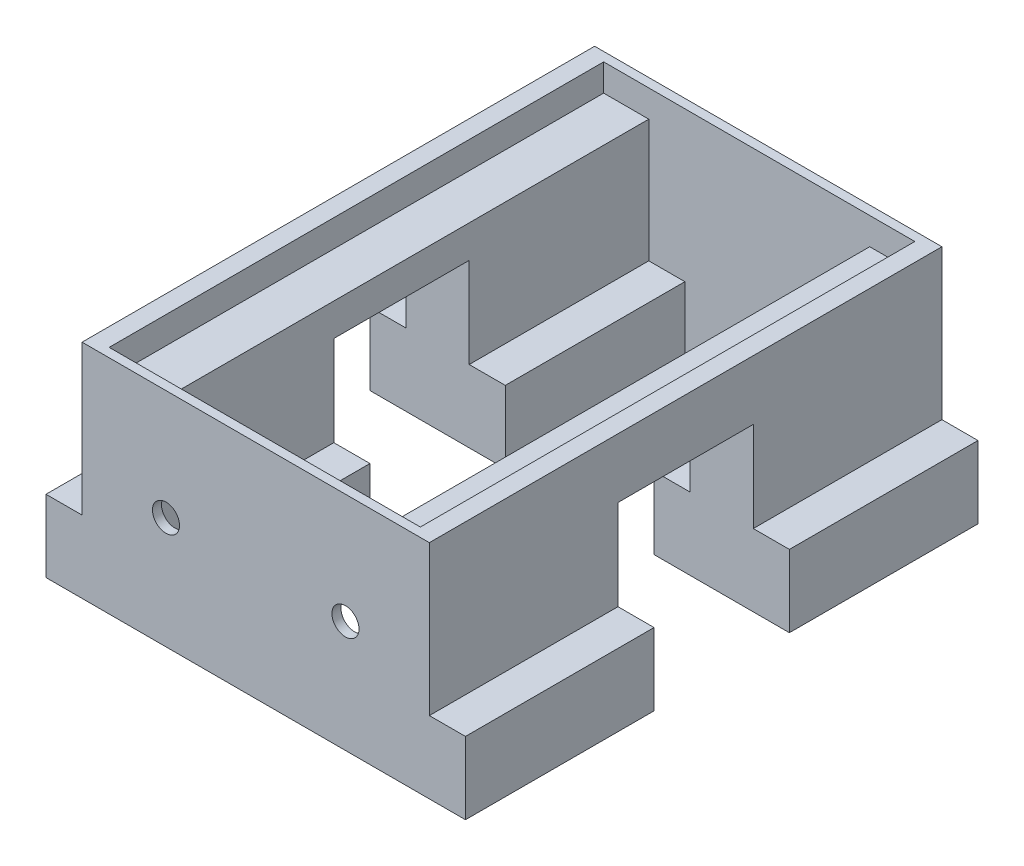
SolidWorks part; units mm, degrees
ref_plane "Front Plane" through (0, 0, 0) normal (0, 0, 1) x (1, 0, 0)
ref_plane "Top Plane" through (0, 0, 0) normal (0, 1, 0) x (1, 0, 0)
ref_plane "Right Plane" through (0, 0, 0) normal (1, 0, 0) x (0, 0, -1)
sketch "Sketch1" plane through (0, 0, 0) normal (0, 0, 1) x (1, 0, 0)
  line L0 (-41.225, 0) -> (-41.225, 40)
  line L1 (-41.225, 40) -> (-61.225, 40)
  line L2 (-61.225, 40) -> (-61.225, 108)
  line L3 (-61.225, 108) -> (-86.225, 108)
  line L4 (-86.225, 108) -> (-86.225, 123)
  line L5 (-86.225, 123) -> (-96.225, 123)
  line L6 (-96.225, 123) -> (-96.225, 40)
  line L7 (-96.225, 40) -> (-116.225, 40)
  line L8 (-116.225, 40) -> (-116.225, 0)
  line L9 (-116.225, 0) -> (-41.225, 0)
  line L10 (0, 0) -> (0, 61.0518) construction
  line L11 (116.225, 0) -> (41.225, 0)
  line L12 (116.225, 40) -> (116.225, 0)
  line L13 (96.225, 40) -> (116.225, 40)
  line L14 (96.225, 123) -> (96.225, 40)
  line L15 (86.225, 123) -> (96.225, 123)
  line L16 (86.225, 108) -> (86.225, 123)
  line L17 (61.225, 108) -> (86.225, 108)
  line L18 (61.225, 40) -> (61.225, 108)
  line L19 (41.225, 40) -> (61.225, 40)
  line L20 (41.225, 0) -> (41.225, 40)
  dimension "D1" = 75
  dimension "D2" = 35
  dimension "D3" = 10
  dimension "D4" = 15
  dimension "D5" = 108
  dimension "D6" = 86.225
  dimension "D7" = 20
  dimension "D8" = 40
  dimension "D9" = 40
extrude "Boss-Extrude1" add sketch "Sketch1" along normal blind 274.05
sketch "Sketch2" plane through (0, 0, 274.05) normal (0, 0, 1) x (1, 0, 0)
  line L0 (-96.225, 123) -> (96.225, 123)
  line L1 (96.225, 123) -> (96.225, 40)
  line L2 (96.225, 40) -> (116.225, 40)
  line L3 (116.225, 40) -> (116.225, 0)
  line L4 (116.225, 0) -> (-116.225, 0)
  line L5 (-116.225, 0) -> (-116.225, 40)
  line L6 (-116.225, 40) -> (-96.225, 40)
  line L7 (-96.225, 40) -> (-96.225, 123)
extrude "Boss-Extrude2" add sketch "Sketch2" along normal blind 5
sketch "Sketch3" plane through (0, 0, 0) normal (0, 0, -1) x (-1, 0, 0)
  line L0 (-96.225, 123) -> (96.225, 123)
  line L1 (96.225, 123) -> (96.225, 40)
  line L2 (96.225, 40) -> (116.225, 40)
  line L3 (116.225, 40) -> (116.225, 0)
  line L4 (116.225, 0) -> (-116.225, 0)
  line L5 (-116.225, 0) -> (-116.225, 40)
  line L6 (-116.225, 40) -> (-96.225, 40)
  line L7 (-96.225, 40) -> (-96.225, 123)
extrude "Boss-Extrude3" add sketch "Sketch3" along normal blind 5
sketch "Sketch4" plane through (116.225, 0, 0) normal (1, 0, 0) x (0, 0, -1)
  line L0 (-174.525, 0) -> (-174.525, 90)
  line L1 (-279.05, 0) -> (5, 0) construction
  line L2 (-174.525, 90) -> (-99.525, 90)
  line L3 (-99.525, 90) -> (-99.525, 0)
  line L4 (-279.05, 40) -> (-279.05, 123) construction
  line L5 (5, 123) -> (5, 40) construction
  line L6 (-174.525, 0) -> (-99.525, 0)
  point P10 (-137.025, 90)
  dimension "D1" = 284.05
  dimension "D2" = 142.025
  dimension "D3" = 90
  dimension "D4" = 75
extrude "Cut-Extrude4" cut sketch "Sketch4" against normal blind 300
sketch "Sketch5" plane through (0, 0, 279.05) normal (0, 0, 1) x (1, 0, 0)
  line L0 (-61.225, 123) -> (-61.225, 140.8453) construction
  line L2 (-96.225, 123) -> (-96.225, 40) construction
  line L3 (0, 0) -> (0, 44.0057) construction
  line L5 (-96.225, 108) -> (-46.2753, 108) construction
  line L6 (96.225, 123) -> (-96.225, 123) construction
  line L7 (61.225, 108) -> (61.225, 130.4463) construction
  line L8 (96.225, 40) -> (96.225, 123) construction
  circle A0 centre (-49.725, 62) radius 7.5
  circle A1 centre (49.725, 62) radius 7.5
  dimension "D5" = 15
  dimension "D8" = 15
  dimension "D1" = 35
  dimension "D2" = 15
  dimension "D3" = 46
  dimension "D4" = 11.5
  dimension "D6" = 35
  dimension "D7" = 11.5
  dimension "D9" = 46
extrude "Cut-Extrude5" cut sketch "Sketch5" against normal blind 10
